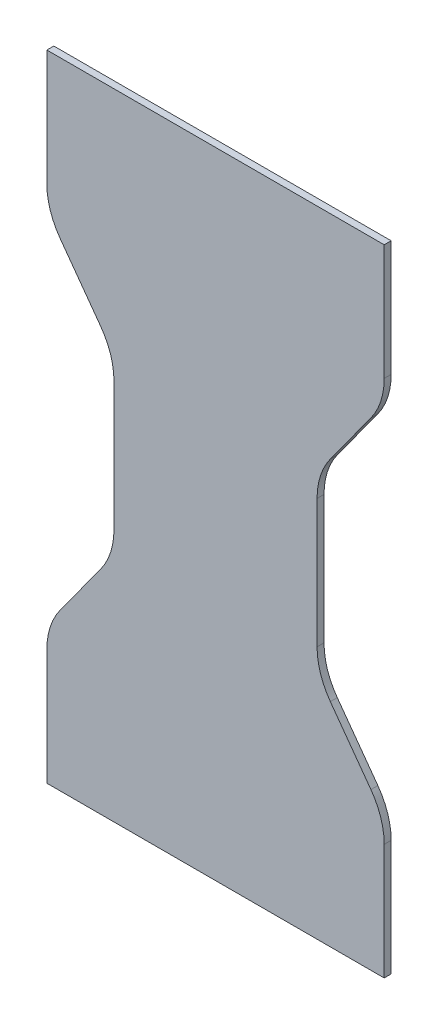
SolidWorks part; units mm, degrees
ref_plane "Alzado" through (0, 0, 0) normal (0, 0, 1) x (1, 0, 0)
ref_plane "Planta" through (0, 0, 0) normal (0, 1, 0) x (1, 0, 0)
ref_plane "Vista lateral" through (0, 0, 0) normal (1, 0, 0) x (0, 0, -1)
sketch "Croquis1" plane through (0, 0, 0) normal (0, 0, 1) x (1, 0, 0)
  line L1 (72.8628, -137.1535) -> (-72.8628, -137.1535)
  line L2 (72.8628, -137.1535) -> (72.8628, -77.4151)
  line L3 (72.8628, 137.1535) -> (-72.8628, 137.1535)
  line L4 (-72.8628, -137.1535) -> (-72.8628, -77.4151)
  line L5 (72.8628, -137.1535) -> (-72.8628, 137.1535) construction
  line L6 (72.8628, 137.1535) -> (-72.8628, -137.1535) construction
  line L7 (-72.8628, 0) -> (72.8628, 0) construction
  line L8 (0, -137.1535) -> (0, 137.1535) construction
  line L9 (-43.8628, -37.5) -> (-43.8628, 37.5)
  line L10 (-43.8628, 37.5) -> (-72.8628, 77.4151)
  line L11 (-43.8628, -37.5) -> (-72.8628, -77.4151)
  line L12 (43.8628, -37.5) -> (72.8628, -77.4151)
  line L13 (43.8628, -37.5) -> (43.8628, 37.5)
  line L14 (43.8628, 37.5) -> (72.8628, 77.4151)
  line L15 (-72.8628, 77.4151) -> (-72.8628, 137.1535)
  line L16 (72.8628, 77.4151) -> (72.8628, 137.1535)
  point P0 (0, 0)
  point P11 (0, 0)
  point P14 (-43.8628, 0)
  dimension "D1" = 145.7256
  dimension "D2" = 274.3069
  dimension "D3" = 144
  dimension "D4" = 144
  dimension "D5" = 29
  dimension "D6" = 75
  dimension "D7" = 137.1535
extrude "Saliente-Extruir1" add sketch "Croquis1" along normal blind 3
fillet "Redondeo1" radius 30 8 edges at (72.8628, 77.4151, 1.5) (43.8628, 37.5, 1.5) (43.8628, -37.5, 1.5) (72.8628, -77.4151, 1.5) (-43.8628, -37.5, 1.5) (-72.8628, -77.4151, 1.5) (-43.8628, 37.5, 1.5) (-72.8628, 77.4151, 1.5)
sketch "Croquis3" plane through (0, 0, 3) normal (0, 0, 1) x (1, 0, 0)
  point P0 (-58, 71)
  point P1 (0, 110)
  point P2 (58, 71)
  point P4 (0, -110)
  point P5 (58, -71)
  point P7 (-58, -71)
  dimension "D1" = 71
  dimension "D2" = 110
  dimension "D3" = 58
  dimension "D6" = 110
  dimension "D4" = 2
  dimension "D5" = 2
